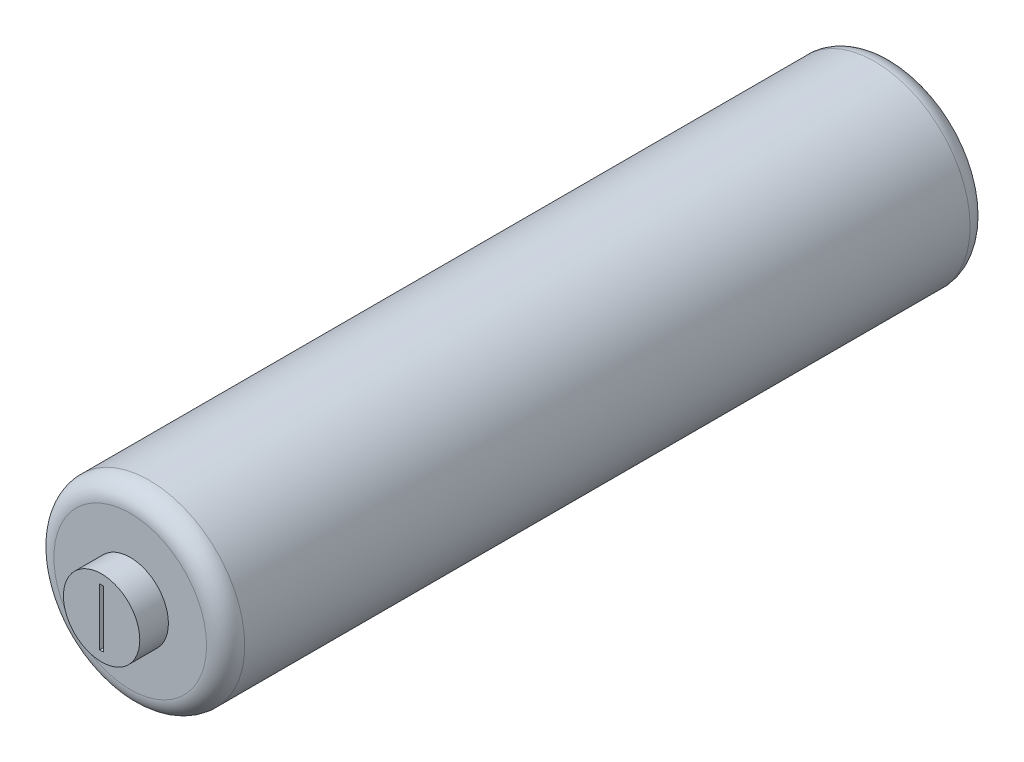
SolidWorks part; units mm, degrees
ref_plane "Front Plane" through (0, 0, 0) normal (0, 0, 1) x (1, 0, 0)
ref_plane "Top Plane" through (0, 0, 0) normal (0, 1, 0) x (1, 0, 0)
ref_plane "Right Plane" through (0, 0, 0) normal (1, 0, 0) x (0, 0, -1)
sketch "Sketch1" plane through (0, 0, 0) normal (0, 0, 1) x (1, 0, 0)
  circle A0 centre (0, 0) radius 250
  dimension "D1" = 500
extrude "Boss-Extrude4" add sketch "Sketch1" along normal mid plane 2000
sketch "Sketch6" plane through (0, 0, 1000) normal (0, 0, 1) x (1, 0, 0)
  circle A0 centre (0, 0) radius 100
extrude "Boss-Extrude5" add sketch "Sketch6" along normal mid plane 150 contours A0
sketch "Sketch8" plane through (0, 0, 1075) normal (0, 0, 1) x (1, 0, 0)
  line L1 (-5, 75) -> (5, 75)
  line L2 (-5, 75) -> (-5, -75)
  line L3 (-5, -75) -> (5, -75)
  line L4 (5, 75) -> (5, -75)
  line L5 (-5, 75) -> (5, -75) construction
  line L6 (-5, -75) -> (5, 75) construction
  point P0 (0, 0)
extrude "Cut-Extrude7" cut sketch "Sketch8" against normal blind 10
mirror "Mirror3" about plane through (0, 0, 0) normal (0, 0, 1) of "Cut-Extrude7", "Boss-Extrude5"
fillet "Fillet1" radius 50 2 edges at (250, 0, -1000) (250, 0, 1000)
